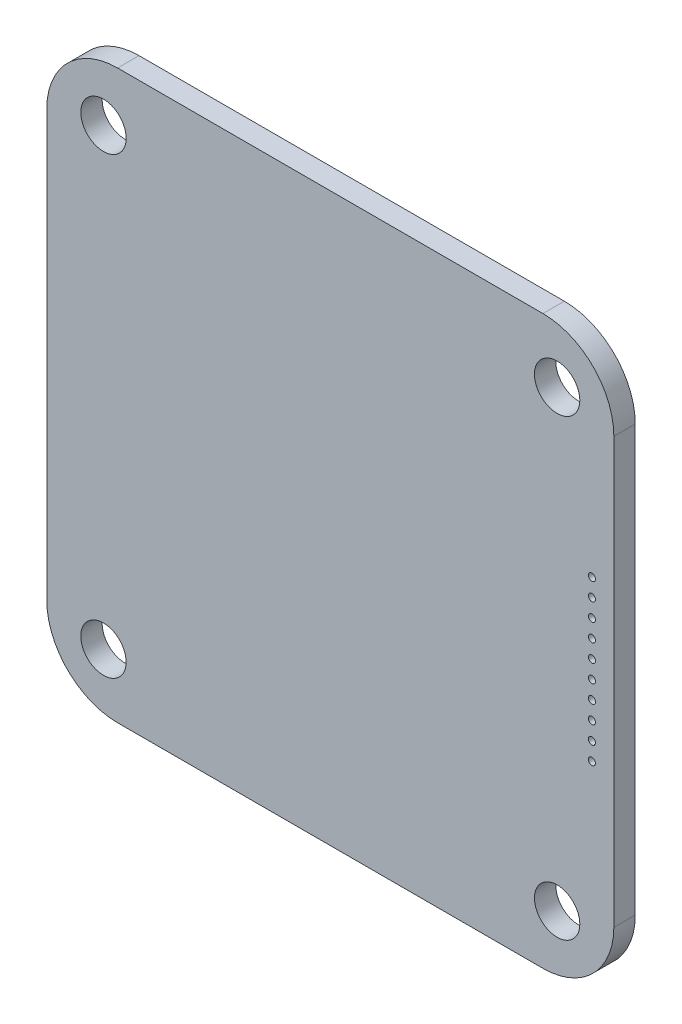
SolidWorks part; units mm, degrees
ref_plane "Front Plane" through (0, 0, 0) normal (0, 0, 1) x (1, 0, 0)
ref_plane "Top Plane" through (0, 0, 0) normal (0, 1, 0) x (1, 0, 0)
ref_plane "Right Plane" through (0, 0, 0) normal (1, 0, 0) x (0, 0, -1)
ref_plane "Plane3" through (0, 0, 8.1) normal (0, 0, 1) x (1, 0, 0)
sketch "Sketch19" plane through (0, 0, 8.1) normal (0, 0, 1) x (1, 0, 0)
  line L0 (41.85, -76.85) -> (71.85, -76.85)
  line L1 (76.85, -71.85) -> (76.85, -41.85)
  line L2 (71.85, -36.85) -> (41.85, -36.85)
  line L3 (36.85, -41.85) -> (36.85, -71.85)
  circle A0 centre (40.85, -72.85) radius 1.6
  circle A1 centre (72.85, -72.85) radius 1.6
  circle A2 centre (75.305, -62.475) radius 0.25
  circle A3 centre (75.305, -61.225) radius 0.25
  circle A4 centre (75.305, -59.975) radius 0.25
  circle A5 centre (75.305, -58.725) radius 0.25
  circle A6 centre (75.305, -57.475) radius 0.25
  circle A7 centre (40.85, -40.85) radius 1.6
  circle A8 centre (75.305, -56.225) radius 0.25
  circle A9 centre (75.305, -54.975) radius 0.25
  circle A10 centre (75.305, -53.725) radius 0.25
  circle A11 centre (75.305, -52.475) radius 0.25
  circle A12 centre (75.305, -51.225) radius 0.25
  circle A13 centre (72.85, -40.85) radius 1.6
  arc A14 (36.85, -71.85) -> (41.85, -76.85) centre (41.85, -71.85) ccw
  arc A15 (71.85, -76.85) -> (76.85, -71.85) centre (71.85, -71.85) ccw
  arc A16 (76.85, -41.85) -> (71.85, -36.85) centre (71.85, -41.85) ccw
  arc A17 (41.85, -36.85) -> (36.85, -41.85) centre (41.85, -41.85) ccw
extrude "Boss-Extrude4" add sketch "Sketch19" against normal blind 1.51 separate body
